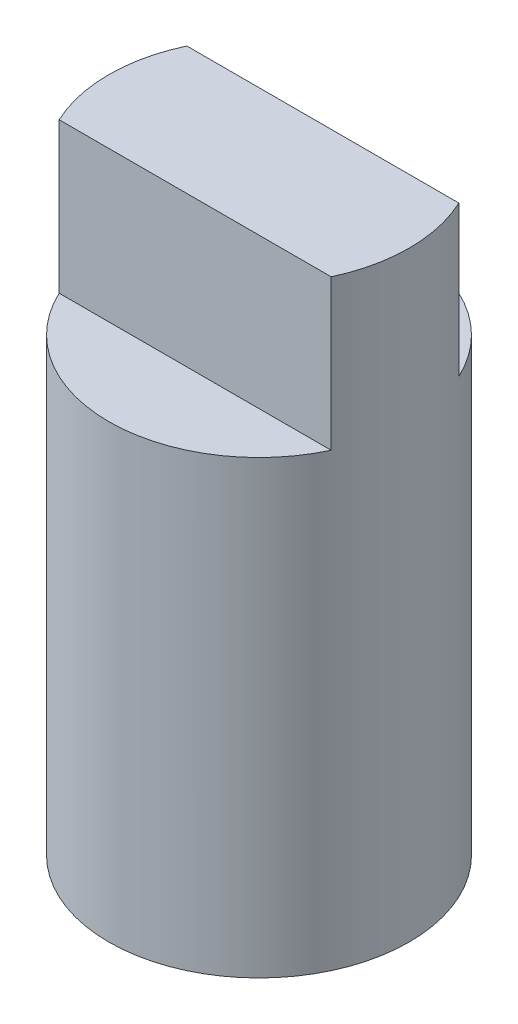
SolidWorks part; units mm, degrees
ref_plane "Front Plane" through (0, 0, 0) normal (0, 0, 1) x (1, 0, 0)
ref_plane "Top Plane" through (0, 0, 0) normal (0, 1, 0) x (1, 0, 0)
ref_plane "Right Plane" through (0, 0, 0) normal (1, 0, 0) x (0, 0, -1)
sketch "Sketch1" plane through (0, 0, 0) normal (0, 1, 0) x (1, 0, 0)
  circle A0 centre (0, 0) radius 25.4
  dimension "D1" = 50.8
extrude "Boss-Extrude1" add sketch "Sketch1" along normal blind 101.6
ref_plane "Plane1" through (25.4, 0, 0) normal (1, 0, 0) x (0, 0, -1)
sketch "Sketch2" plane through (25.4, 0, 0) normal (1, 0, 0) x (0, 0, -1)
  line L0 (25.4, 101.6) -> (-25.4, 101.6) construction
  line L1 (-10.795, 101.6) -> (-25.4, 101.6)
  line L2 (-10.795, 101.6) -> (-10.795, 76.2)
  line L3 (-10.795, 76.2) -> (-25.4, 76.2)
  line L4 (-25.4, 101.6) -> (-25.4, 76.2)
  line L5 (25.4, 0) -> (25.4, 101.6) construction
  line L6 (10.795, 101.6) -> (25.4, 101.6)
  line L7 (10.795, 101.6) -> (10.795, 76.2)
  line L8 (10.795, 76.2) -> (25.4, 76.2)
  line L9 (25.4, 101.6) -> (25.4, 76.2)
  line L10 (-25.4, 101.6) -> (-25.4, 0) construction
  point P12 (-25.4, 101.6)
  dimension "D1" = 21.59
  dimension "D2" = 25.4
extrude "Cut-Extrude1" cut sketch "Sketch2" against normal up to next
